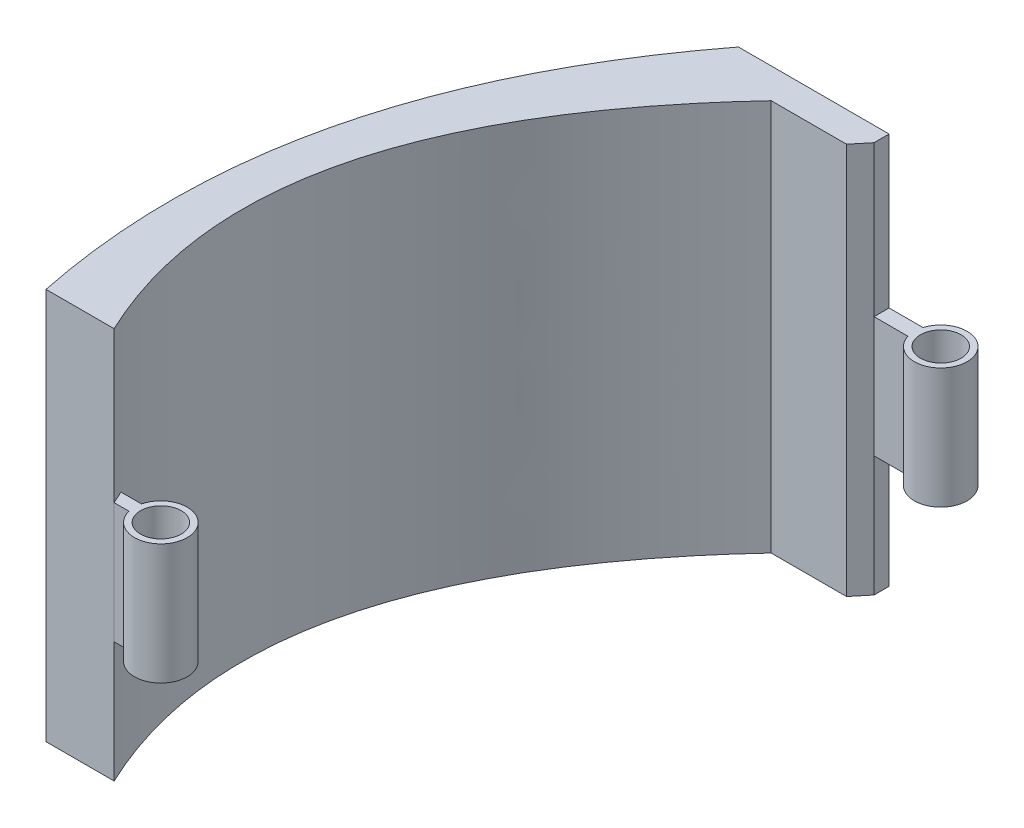
SolidWorks part; units mm, degrees
ref_plane "Front Plane" through (0, 0, 0) normal (0, 0, 1) x (1, 0, 0)
ref_plane "Top Plane" through (0, 0, 0) normal (0, 1, 0) x (1, 0, 0)
ref_plane "Right Plane" through (0, 0, 0) normal (1, 0, 0) x (0, 0, -1)
sketch "Sketch1" plane through (0, 0, 0) normal (0, 1, 0) x (1, 0, 0)
  line L0 (4.5285, 36.9072) -> (14.5285, 36.9072)
  line L1 (14.5285, 36.9072) -> (14.5285, 35.9072)
  line L2 (14.5285, 35.9072) -> (13.702, 34.9072)
  line L3 (13.702, 34.9072) -> (8.702, 34.9072)
  line L4 (-4.5191, 0) -> (0, 0)
  spline S0 degree 2 poles (-4.5191, 0) (-8.6002, 19.7976) (4.5285, 36.9072) knots 0 0 0 1 1 1
  spline S1 degree 2 poles (8.702, 34.9072) (-8.0479, 17.0045) (0, 0) knots 0 0 0 1 1 1
  dimension "D6" = 13.702
  dimension "D10" = 5.3858
  dimension "D1" = 38
  dimension "D2" = 10
  dimension "D3" = 5
  dimension "D4" = 1
  dimension "D5" = 2
  dimension "D7" = 3.3628
  dimension "D8" = 1.3462
  dimension "D9" = 4.5191
  dimension "D11" = 4.628
  dimension "D12" = 12.1592
extrude "Boss-Extrude1" add sketch "Sketch1" along normal blind 26
sketch "Sketch2" plane through (0, 26, 0) normal (0, 1, 0) x (1, 0, 0)
  line L0 (14.5285, 36.9072) -> (16.7785, 36.9072)
  line L2 (16.7785, 35.9072) -> (14.5285, 35.9072)
  line L3 (14.5285, 35.9072) -> (14.5285, 36.9072)
  arc A0 (16.7785, 35.9072) -> (16.7785, 36.9072) centre (18.4556, 36.4072) ccw
  point P3 (15.3746, 43.0611)
  point P7 (0, 0)
  point P8 (17.4047, 41.0374)
  point P9 (16.8796, 44.3821)
  point P11 (16.0289, 43.8914)
  dimension "D1" = 1.75
  dimension "D2" = 2.25
extrude "Boss-Extrude2" add sketch "Sketch2" against normal blind 8 from offset 10 offset against normal yes
sketch "Sketch3" plane through (0, 16, 0) normal (0, 1, 0) x (1, 0, 0)
  circle A0 centre (18.4556, 36.4072) radius 1.35
  dimension "D1" = 2.7
extrude "Cut-Extrude1" cut sketch "Sketch3" against normal through all
sketch "Sketch4" plane through (0, 26, 0) normal (0, 1, 0) x (1, 0, 0)
  line L0 (-0.3801, 0.8352) -> (0.987, 0.8352)
  line L1 (0.987, 0) -> (0, 0)
  arc A0 (0.987, 0) -> (0.987, 0.8352) centre (2.6864, 0.4176) ccw
  parabola Q1 (0, 0) -> (8.702, 34.9072) focus (9.436, 10.6955) apex (-2.5961, 10.2597) construction
  parabola Q24 (0, 0) -> (8.702, 34.9072) focus (9.436, 10.6955) apex (-2.5961, 10.2597) construction
  spline S0 degree 1 poles (-0.3801, 0.8352) (0, 0) knots 0 0 1 1
  dimension "D1" = 1.75
extrude "Boss-Extrude3" add sketch "Sketch4" against normal blind 8 from offset 10 separate body offset against normal yes
sketch "Sketch5" plane through (0, 16, 0) normal (0, 1, 0) x (1, 0, 0)
  circle A0 centre (2.6864, 0.4176) radius 1.35
  dimension "D1" = 2.7
extrude "Cut-Extrude2" cut sketch "Sketch5" against normal through all
